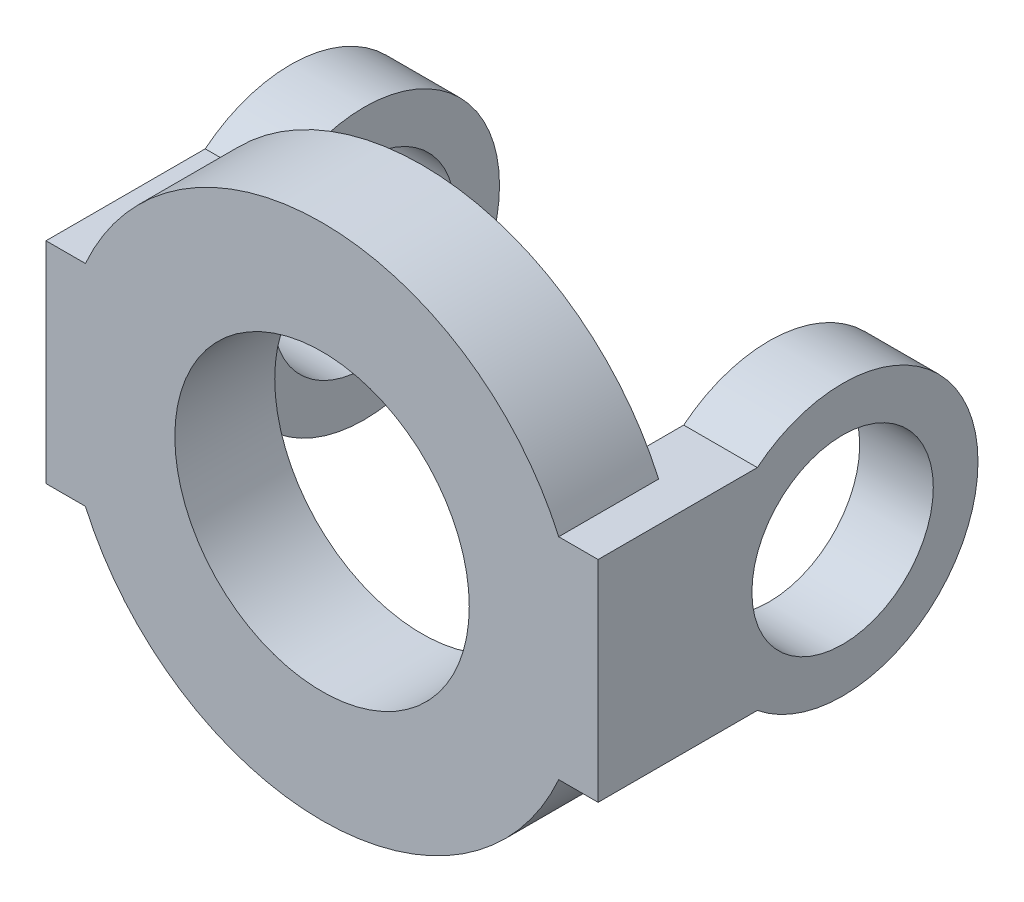
SolidWorks part; units mm, degrees
ref_plane "前视基准面" through (0, 0, 0) normal (0, 0, 1) x (1, 0, 0)
ref_plane "上视基准面" through (0, 0, 0) normal (0, 1, 0) x (1, 0, 0)
ref_plane "右视基准面" through (0, 0, 0) normal (1, 0, 0) x (0, 0, -1)
sketch "Sketch1" plane through (0, 0, 0) normal (0, 0, 1) x (1, 0, 0)
  line L0 (-39.1918, 40) -> (39.1918, 40) construction
  line L1 (-105, -40) -> (-90.0125, -40)
  line L2 (-105, -40) -> (-105, 40)
  line L3 (-105, 40) -> (-90.0125, 40)
  line L4 (105, -40) -> (105, 40)
  line L5 (-105, -40) -> (105, 40) construction
  line L6 (-105, 40) -> (105, -40) construction
  line L7 (90.0125, -40) -> (105, -40)
  line L8 (90.0125, 40) -> (105, 40)
  arc A0 (90.0125, 40) -> (-90.0125, 40) centre (0, 0) ccw
  circle A1 centre (0, 0) radius 56
  arc A2 (-90.0125, -40) -> (90.0125, -40) centre (0, 0) ccw
  dimension "D1" = 197
  dimension "D2" = 112
  dimension "D3" = 80
  dimension "D4" = 210
extrude "Extrude1" add sketch "Sketch1" along normal blind 38
sketch "Sketch2" plane through (-105, 0, 0) normal (-1, 0, 0) x (0, 0, 1)
  line L0 (0, 40) -> (-22.5616, 40)
  line L1 (-22.5616, -40) -> (0, -40)
  line L2 (0, -40) -> (0, 40)
  line L3 (38, 40) -> (0, 40) construction
  arc A0 (-22.5616, 40) -> (-22.5616, -40) centre (-55, 0) ccw
  dimension "D1" = 103
  dimension "D2" = 55
extrude "Extrude2" add sketch "Sketch2" against normal blind 28
mirror "Mirror1" about plane through (0, 0, 0) normal (1, 0, 0) of "Extrude2"
sketch "Sketch3" plane through (-105, 0, 0) normal (-1, 0, 0) x (0, 0, 1)
  circle A0 centre (-55, 0) radius 34.5
  dimension "D1" = 69
extrude "Extrude3" cut sketch "Sketch3" against normal through all
